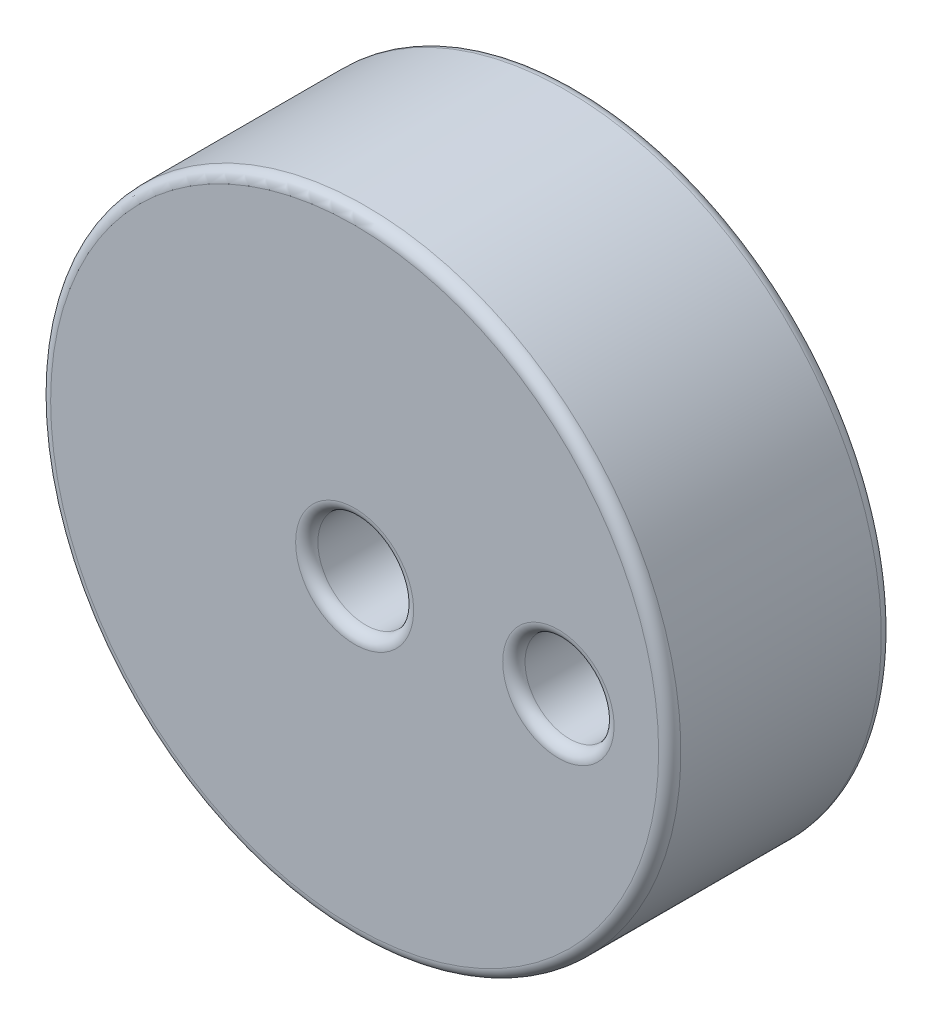
SolidWorks part; units mm, degrees
ref_plane "Front Plane" through (0, 0, 0) normal (0, 0, 1) x (1, 0, 0)
ref_plane "Top Plane" through (0, 0, 0) normal (0, 1, 0) x (1, 0, 0)
ref_plane "Right Plane" through (0, 0, 0) normal (1, 0, 0) x (0, 0, -1)
sketch "Sketch1" plane through (0, 0, 0) normal (0, 1, 0) x (1, 0, 0)
  line L0 (0, 0) -> (0, 47062.5796) construction
  line L1 (0, 0) -> (2.15, 0) construction
  line L3 (0, 3.3609) -> (3.6, 3.3609) construction
  line L4 (14.15, -4.5) -> (2.15, -4.5)
  line L5 (14.15, -4.5) -> (14.15, 1.5)
  line L6 (14.15, 1.5) -> (2.15, 1.5)
  line L7 (2.15, -4.5) -> (2.15, 1.5)
  line L8 (14.15, -4.5) -> (2.15, 1.5) construction
  line L9 (14.15, 1.5) -> (2.15, -4.5) construction
  line L10 (14.15, 1.5) -> (3.6, 1.5)
  line L11 (14.15, 1.5) -> (14.15, 5.5)
  line L12 (14.15, 5.5) -> (3.6, 5.5)
  line L13 (3.6, 1.5) -> (3.6, 5.5)
  dimension "D1" = 2.15
  dimension "D2" = 3.6
  dimension "D3" = 6
  dimension "D4" = 12
  dimension "D5" = 4
  dimension "D6" = 10.55
  dimension "D7" = 12
revolve "Revolve1" add sketch "Sketch1" angle 360 about L0
sketch "Sketch2" plane through (0, 0, -5.5) normal (0, 0, -1) x (-1, 0, 0)
  line L0 (-11.15, 0) -> (-14.15, 0) construction
  circle A1 centre (-9.15, 0) radius 2
  circle A2 centre (0, 0) radius 14.15 construction
  dimension "D1" = 4
  dimension "D2" = 3
extrude "Cut-Extrude1" cut sketch "Sketch2" against normal blind 10
fillet "Fillet2" radius 0.5 7 edges at (7.15, 0, 4.5) (7.15, 0, -5.5) (2.15, 0, -1.5) (3.6, 0, -5.5) (14.15, 0, -5.5) (14.15, 0, 4.5) (2.15, 0, 4.5)
